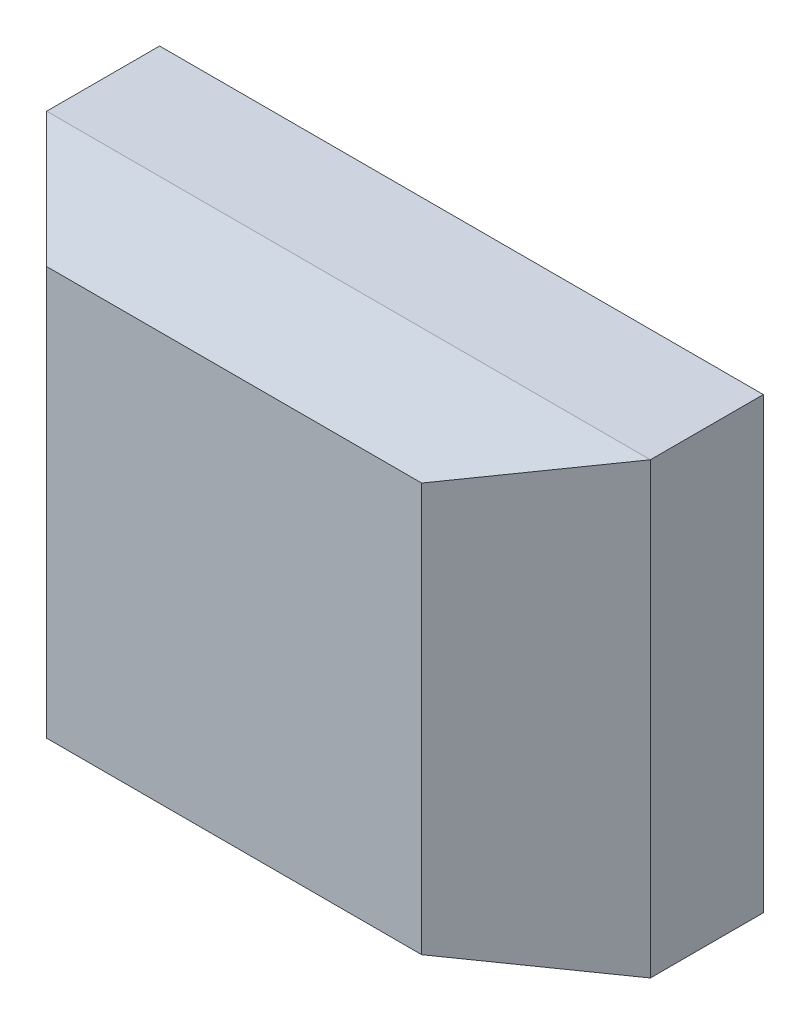
SolidWorks part; units mm, degrees
ref_plane "Front Plane" through (0, 0, 0) normal (0, 0, 1) x (1, 0, 0)
ref_plane "Top Plane" through (0, 0, 0) normal (0, 1, 0) x (1, 0, 0)
ref_plane "Right Plane" through (0, 0, 0) normal (1, 0, 0) x (0, 0, -1)
sketch "Sketch2" plane through (0, 0, 0) normal (0, 1, 0) x (1, 0, 0)
  line L0 (-2.085, 0) -> (2.085, 0)
  line L1 (-2.085, 0) -> (-2.085, -1.57) construction
  line L2 (2.085, 0) -> (2.085, -0.78)
  line L3 (-2.085, -1.57) -> (4.3151, -1.57) construction
  line L4 (2.085, -0.78) -> (1.295, -1.57)
  line L5 (2.085, -0.78) -> (2.085, -1.1931) construction
  line L6 (0, 0) -> (0, -1.57) construction
  line L7 (1.295, -1.57) -> (-1.295, -1.57)
  line L8 (-2.085, -0.78) -> (-1.295, -1.57)
  line L9 (-2.085, 0) -> (-2.085, -0.78)
  point P4 (0, 0)
  dimension "D1" = 4.17
  dimension "D2" = 1.57
  dimension "D3" = 0.78
  dimension "D4" = 135
  dimension "D5" = 45
extrude "Boss-Extrude1" add sketch "Sketch2" against normal blind 3.1
sketch "Sketch3" plane through (0, -3.1, 0) normal (0, -1, 0) x (1, 0, 0)
  line L0 (0, 1.57) -> (0, 0.78) construction
  line L1 (-1.295, 1.57) -> (1.295, 1.57) construction
  line L2 (0, 0.78) -> (0, 0.56) construction
  line L3 (0, 0.56) -> (1.27, 0.56) construction
  line L4 (-0.24, 0.34) -> (0.24, 0.34)
  line L5 (-0.24, 0.34) -> (-0.24, 0.78)
  line L6 (-0.24, 0.78) -> (0.24, 0.78)
  line L7 (0.24, 0.34) -> (0.24, 0.78)
  line L8 (-0.24, 0.34) -> (0.24, 0.78) construction
  line L9 (-0.24, 0.78) -> (0.24, 0.34) construction
  line L10 (-1.03, 0.34) -> (-1.03, 0.78)
  line L11 (1.03, 0.34) -> (1.51, 0.34)
  line L12 (1.03, 0.34) -> (1.03, 0.78)
  line L13 (1.03, 0.78) -> (1.51, 0.78)
  line L14 (1.51, 0.34) -> (1.51, 0.78)
  line L15 (1.03, 0.34) -> (1.51, 0.78) construction
  line L16 (1.03, 0.78) -> (1.51, 0.34) construction
  line L17 (-1.03, 0.34) -> (-1.51, 0.34)
  line L18 (-1.51, 0.34) -> (-1.51, 0.78)
  line L19 (-1.03, 0.78) -> (-1.51, 0.78)
  dimension "D1" = 0.22
  dimension "D2" = 0.79
  dimension "D3" = 0.48
  dimension "D4" = 0.44
  dimension "D5" = 1.27
  dimension "D6" = 0.48
  dimension "D7" = 0.44
extrude "Boss-Extrude2" [suppressed] add sketch "Sketch3" along normal blind 15.24
sketch "Sketch4" plane through (2.085, 0, 0) normal (1, 0, 0) x (0, 0, -1)
  line L0 (-0.78, 0) -> (-2.735, -0.3447)
  line L1 (-0.78, -3.1) -> (-2.5824, -2.7822)
  line L2 (-2.5824, -2.7822) -> (-2.5824, -3.1)
  line L3 (-2.5824, -3.1) -> (-0.78, -3.1)
  line L4 (-2.735, -0.3447) -> (-2.735, 0)
  line L5 (-2.735, 0) -> (-0.78, 0)
  dimension "D1" = 10
  dimension "D2" = 10
extrude "Cut-Extrude1" cut sketch "Sketch4" against normal through all
